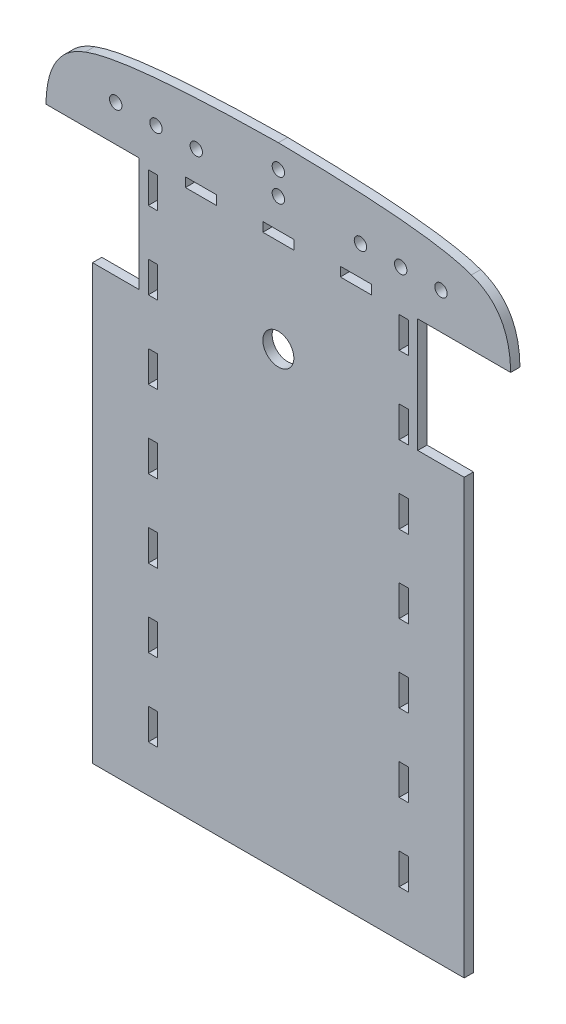
SolidWorks part; units mm, degrees
ref_plane "Plan de face" through (0, 0, 0) normal (0, 0, 1) x (1, 0, 0)
ref_plane "Plan de dessus" through (0, 0, 0) normal (0, 1, 0) x (1, 0, 0)
ref_plane "Plan de droite" through (0, 0, 0) normal (1, 0, 0) x (0, 0, -1)
sketch "Esquisse1" plane through (0, 0, 0) normal (0, 0, 1) x (1, 0, 0)
  line L0 (78.1094, -135) -> (-41.8906, -135)
  line L1 (-41.8906, -135) -> (-41.8906, 5)
  line L2 (-41.8906, 5) -> (-26.8906, 5)
  line L3 (-26.8906, 5) -> (-26.8906, 41.7954)
  line L4 (-26.8906, 41.7954) -> (-56.8906, 41.7954)
  line L5 (78.1094, -135) -> (78.1094, 5)
  line L6 (78.1094, 5) -> (63.1094, 5)
  line L7 (63.1094, 5) -> (63.1094, 41.7954)
  line L8 (63.1094, 41.7954) -> (93.1094, 41.7954)
  line L9 (-56.8906, 41.7954) -> (-56.7469, 58.2948) construction
  line L10 (-56.7469, 58.2948) -> (-44.2159, 62.7289) construction
  line L11 (18.1094, -135) -> (18.1094, 139.9257) construction
  line L12 (-44.2159, 62.7289) -> (-30.5282, 67.9341) construction
  line L13 (-30.5282, 67.9341) -> (18.1094, 68.5507) construction
  line L14 (93.1094, 41.7954) -> (92.9656, 58.2948) construction
  line L15 (92.9656, 58.2948) -> (80.4346, 62.7289) construction
  line L16 (80.4346, 62.7289) -> (66.7469, 67.9341) construction
  line L17 (66.7469, 67.9341) -> (18.1094, 68.5507) construction
  circle A0 centre (18.1094, 10.8116) radius 5
  circle A1 centre (18.1094, 53.5507) radius 2
  circle A2 centre (-8.3906, 53.5507) radius 2
  circle A3 centre (-34.3906, 53.5507) radius 2
  circle A4 centre (70.6094, 53.5507) radius 2
  circle A5 centre (44.6094, 53.5507) radius 2
  circle A6 centre (18.1094, 61.0555) radius 2
  circle A7 centre (-21.3906, 53.5507) radius 2
  circle A8 centre (57.6094, 53.5507) radius 2
  spline S0 degree 2 poles (-56.8906, 41.7954) (-56.7469, 58.2948) (-44.2159, 62.7289) knots 0 0 0 1 1 1
  spline S1 degree 2 poles (-44.2159, 62.7289) (-30.5282, 67.9341) (18.1094, 68.5507) knots 0 0 0 1 1 1
  spline S2 degree 2 poles (93.1094, 41.7954) (92.9656, 58.2948) (80.4346, 62.7289) knots 0 0 0 1 1 1
  spline S3 degree 2 poles (80.4346, 62.7289) (66.7469, 67.9341) (18.1094, 68.5507) knots 0 0 0 1 1 1
  dimension "D4" = 10
  dimension "D8" = 4
  dimension "D9" = 4
  dimension "D10" = 4
  dimension "D5" = 4
  dimension "D12" = 4
  dimension "D1" = 120
  dimension "D2" = 140
  dimension "D3" = 15
  dimension "D6" = 26.5
  dimension "D7" = 26
  dimension "D11" = 15
  dimension "D13" = 13
extrude "Boss.-Extru.1" add sketch "Esquisse1" along normal blind 3
sketch "Esquisse3" plane through (0, 0, 3) normal (0, 0, 1) x (1, 0, 0)
  line L0 (-41.8906, -135) -> (78.1094, -135) construction
  line L1 (-23.8906, -120) -> (-20.8906, -120)
  line L2 (-23.8906, -120) -> (-23.8906, -110)
  line L3 (-23.8906, -110) -> (-20.8906, -110)
  line L4 (-20.8906, -120) -> (-20.8906, -110)
  line L5 (-41.8906, 5) -> (-41.8906, -135) construction
  line L6 (-23.8906, -95) -> (-23.8906, -85)
  line L7 (-23.8906, -95) -> (-20.8906, -95)
  line L8 (-20.8906, -95) -> (-20.8906, -85)
  line L9 (-23.8906, -85) -> (-20.8906, -85)
  line L10 (-23.8906, -70) -> (-23.8906, -60)
  line L11 (-23.8906, -70) -> (-20.8906, -70)
  line L12 (-20.8906, -70) -> (-20.8906, -60)
  line L13 (-23.8906, -60) -> (-20.8906, -60)
  line L14 (-23.8906, -45) -> (-23.8906, -35)
  line L15 (-23.8906, -45) -> (-20.8906, -45)
  line L16 (-20.8906, -45) -> (-20.8906, -35)
  line L17 (-23.8906, -35) -> (-20.8906, -35)
  line L18 (-23.8906, -20) -> (-23.8906, -10)
  line L19 (-23.8906, -20) -> (-20.8906, -20)
  line L20 (-20.8906, -20) -> (-20.8906, -10)
  line L21 (-23.8906, -10) -> (-20.8906, -10)
  line L22 (-23.8906, 5) -> (-23.8906, 15)
  line L23 (-23.8906, 5) -> (-20.8906, 5)
  line L24 (-20.8906, 5) -> (-20.8906, 15)
  line L25 (-23.8906, 15) -> (-20.8906, 15)
  line L26 (-23.8906, 30) -> (-23.8906, 40)
  line L27 (-23.8906, 30) -> (-20.8906, 30)
  line L28 (-20.8906, 30) -> (-20.8906, 40)
  line L29 (-23.8906, 40) -> (-20.8906, 40)
  line L30 (-23.8906, -120) -> (-23.8906, -95) construction
  line L31 (18.1094, -135) -> (18.1094, 40) construction
  line L32 (60.1094, -20) -> (57.1094, -20)
  line L33 (57.1094, -20) -> (57.1094, -10)
  line L34 (60.1094, -10) -> (57.1094, -10)
  line L35 (60.1094, -20) -> (60.1094, -10)
  line L36 (60.1094, 5) -> (57.1094, 5)
  line L37 (57.1094, 5) -> (57.1094, 15)
  line L38 (60.1094, 15) -> (57.1094, 15)
  line L39 (60.1094, 5) -> (60.1094, 15)
  line L40 (60.1094, 30) -> (57.1094, 30)
  line L41 (57.1094, 30) -> (57.1094, 40)
  line L42 (60.1094, 40) -> (57.1094, 40)
  line L43 (60.1094, 30) -> (60.1094, 40)
  line L44 (60.1094, -70) -> (57.1094, -70)
  line L45 (57.1094, -70) -> (57.1094, -60)
  line L46 (60.1094, -60) -> (57.1094, -60)
  line L47 (60.1094, -70) -> (60.1094, -60)
  line L48 (60.1094, -45) -> (57.1094, -45)
  line L49 (57.1094, -45) -> (57.1094, -35)
  line L50 (60.1094, -35) -> (57.1094, -35)
  line L51 (60.1094, -45) -> (60.1094, -35)
  line L52 (60.1094, -95) -> (57.1094, -95)
  line L53 (57.1094, -95) -> (57.1094, -85)
  line L54 (60.1094, -85) -> (57.1094, -85)
  line L55 (60.1094, -95) -> (60.1094, -85)
  line L56 (60.1094, -110) -> (57.1094, -110)
  line L57 (57.1094, -120) -> (57.1094, -110)
  line L58 (60.1094, -120) -> (57.1094, -120)
  line L59 (60.1094, -120) -> (60.1094, -110)
  line L60 (-26.8906, 41.7954) -> (-26.8906, 5) construction
  line L61 (-11.8906, 41) -> (-1.8906, 41)
  line L62 (-11.8906, 41) -> (-11.8906, 44)
  line L63 (-11.8906, 44) -> (-1.8906, 44)
  line L64 (-1.8906, 41) -> (-1.8906, 44)
  line L65 (13.1094, 41) -> (13.1094, 44)
  line L66 (13.1094, 41) -> (23.1094, 41)
  line L67 (23.1094, 41) -> (23.1094, 44)
  line L68 (13.1094, 44) -> (23.1094, 44)
  line L69 (38.1094, 41) -> (38.1094, 44)
  line L70 (38.1094, 41) -> (48.1094, 41)
  line L71 (48.1094, 41) -> (48.1094, 44)
  line L72 (38.1094, 44) -> (48.1094, 44)
  line L73 (-11.8906, 41) -> (13.1094, 41) construction
  dimension "D1" = 3
  dimension "D2" = 10
  dimension "D3" = 15
  dimension "D4" = 18
  dimension "D6" = 25
  dimension "D7" = 3
  dimension "D8" = 10
  dimension "D9" = 1
  dimension "D10" = 15
  dimension "D12" = 25
  dimension "D5" = 7
  dimension "D11" = 3
extrude "Enlèv. mat.-Extru.1" cut sketch "Esquisse3" against normal through all
